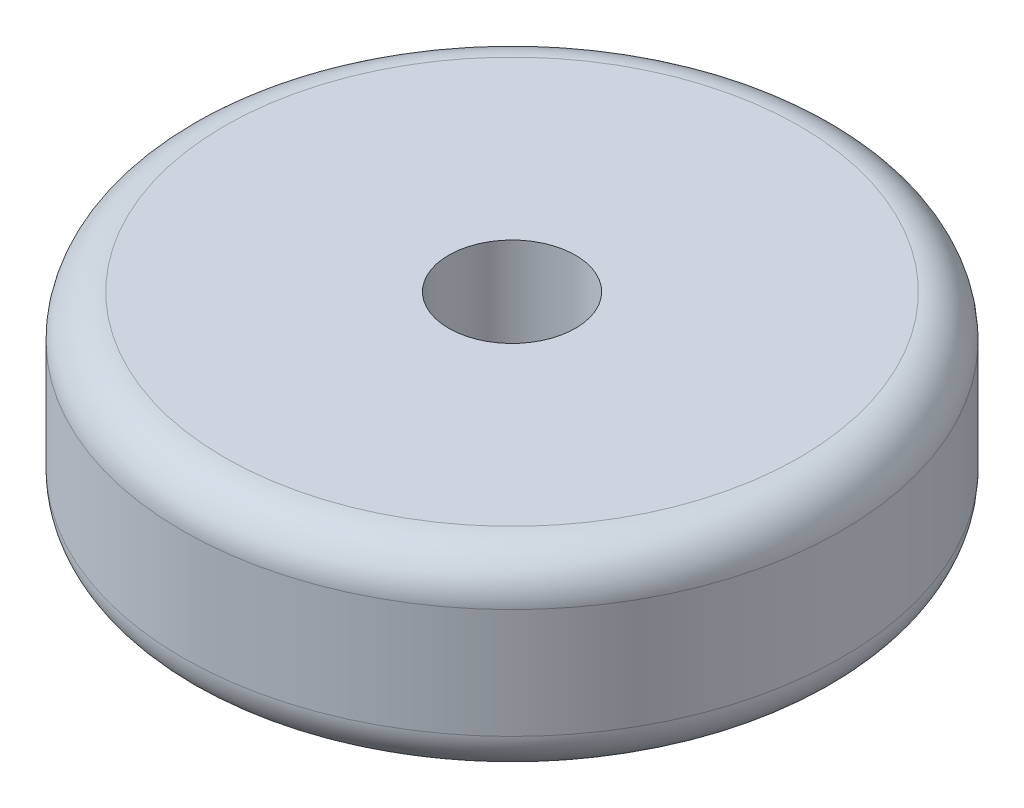
SolidWorks part; units mm, degrees
ref_plane "Front Plane" through (0, 0, 0) normal (0, 0, 1) x (1, 0, 0)
ref_plane "Top Plane" through (0, 0, 0) normal (0, 1, 0) x (1, 0, 0)
ref_plane "Right Plane" through (0, 0, 0) normal (1, 0, 0) x (0, 0, -1)
sketch "Sketch1" plane through (0, 0, 0) normal (0, 1, 0) x (1, 0, 0)
  circle A0 centre (0, 0) radius 39
  dimension "D1" = 78
extrude "Boss-Extrude1" add sketch "Sketch1" along normal mid plane 23
fillet "Fillet1" radius 5 2 edges at (0, -11.5, 39) (0, 11.5, 39)
sketch "Sketch2" plane through (0, 11.5, 0) normal (0, 1, 0) x (1, 0, 0)
  circle A0 centre (0, 0) radius 7.5
  dimension "D1" = 15
extrude "Cut-Extrude1" cut sketch "Sketch2" against normal through all both and the other way through all
